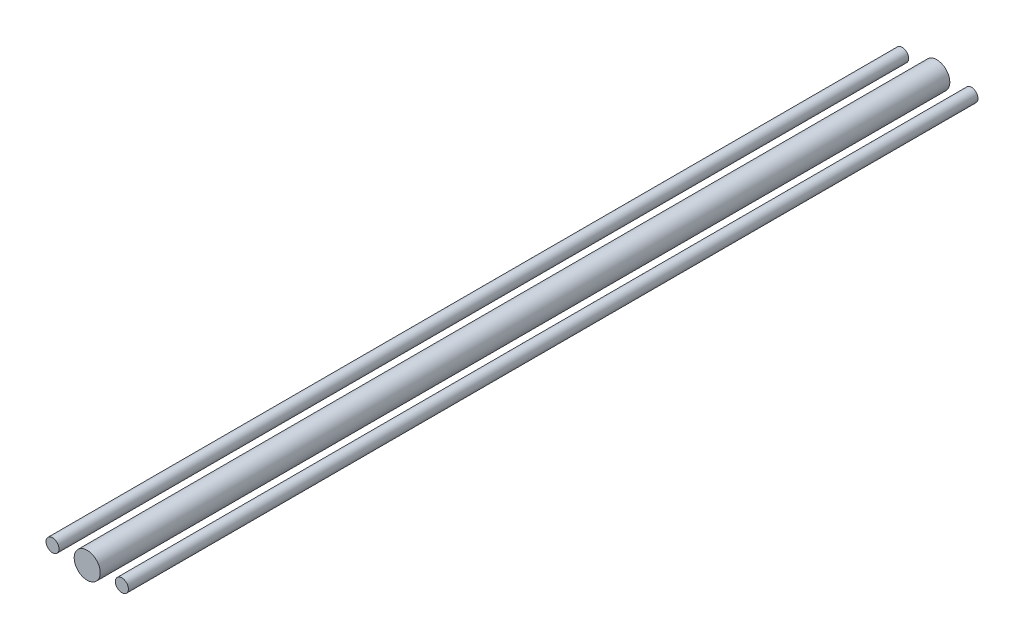
SolidWorks part; units mm, degrees
ref_plane "前视基准面" through (0, 0, 0) normal (0, 0, 1) x (1, 0, 0)
ref_plane "上视基准面" through (0, 0, 0) normal (0, 1, 0) x (1, 0, 0)
ref_plane "右视基准面" through (0, 0, 0) normal (1, 0, 0) x (0, 0, -1)
other "Configuration Table"
sketch "草图1" plane through (0, 0, 0) normal (0, 0, 1) x (1, 0, 0)
  circle A0 centre (0, 0) radius 15
  dimension "D1" = 30
extrude "凸台-拉伸1" add sketch "草图1" along normal blind 1000
sketch "草图6" plane through (0, 0, 0) normal (0, 0, -1) x (-1, 0, 0)
  line L0 (0, 0) -> (-40, 0) construction
  line L1 (0, 0) -> (40, 0) construction
  circle A0 centre (-40, 0) radius 7.5
  circle A1 centre (40, 0) radius 7.5
  dimension "D3" = 15
  dimension "D4" = 15
  dimension "D1" = 40
  dimension "D2" = 40
extrude "凸台-拉伸2" add sketch "草图6" against normal blind 1000 separate body
sketch "草图7" plane through (-56.909, 0, 0) normal (-1, 0, 0) x (0, 0, 1)
  line L5 (20, -53.8253) -> (20, 33.2842)
  line L6 (20, 33.2842) -> (-23.3736, 33.2842)
  line L7 (20, 33.2842) -> (20, -53.8253)
  line L8 (20, -53.8253) -> (-23.3736, -53.8253)
  line L9 (-23.3736, 33.2842) -> (-23.3736, -53.8253)
extrude "切除-拉伸1" cut sketch "草图7" against normal through all both and the other way through all contours L6 L9 L8 L5
